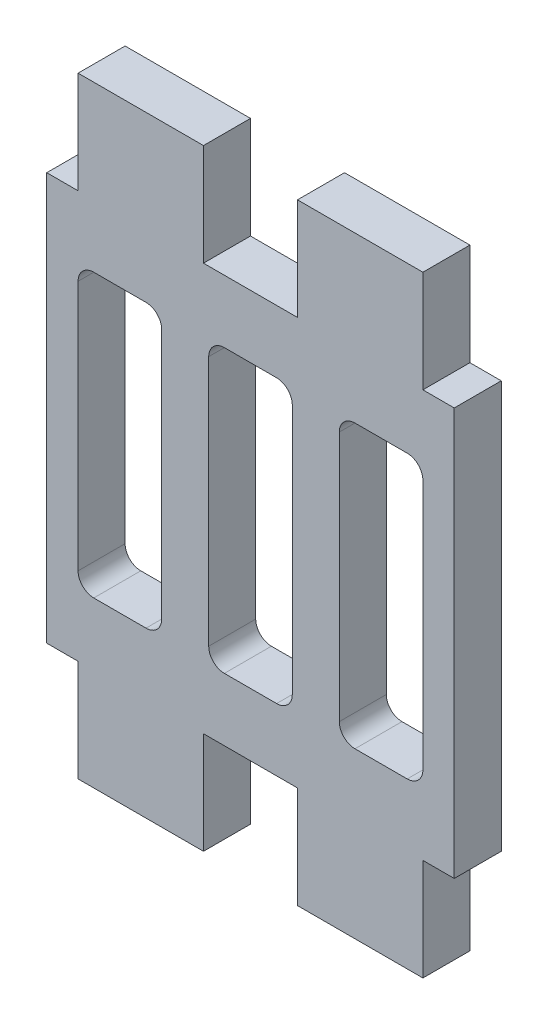
SolidWorks part; units mm, degrees
ref_plane "前视基准面" through (0, 0, 0) normal (0, 0, 1) x (1, 0, 0)
ref_plane "上视基准面" through (0, 0, 0) normal (0, 1, 0) x (1, 0, 0)
ref_plane "右视基准面" through (0, 0, 0) normal (1, 0, 0) x (0, 0, -1)
sketch "草图1" plane through (0, 0, 0) normal (0, 0, 1) x (1, 0, 0)
  line L0 (-11, 13) -> (-3, 13)
  line L1 (-13, 13) -> (13, 13)
  line L2 (-13, 13) -> (-13, -13)
  line L3 (-13, -13) -> (13, -13)
  line L4 (13, 13) -> (13, -13)
  line L5 (0, -13) -> (0, 13) construction
  line L6 (-13, 0) -> (13, 0) construction
  line L7 (-11, 13) -> (-11, 19.5)
  line L8 (-3, 13) -> (-3, 19.5)
  line L9 (-11, 19.5) -> (-3, 19.5)
  line L10 (3, 13) -> (11, 13)
  line L11 (3, 13) -> (3, 19.5)
  line L12 (11, 13) -> (11, 19.5)
  line L13 (3, 19.5) -> (11, 19.5)
  line L22 (3, -19.5) -> (11, -19.5)
  line L23 (11, -13) -> (11, -19.5)
  line L24 (3, -13) -> (3, -19.5)
  line L25 (3, -13) -> (11, -13)
  line L26 (-11, -19.5) -> (-3, -19.5)
  line L27 (-3, -13) -> (-3, -19.5)
  line L28 (-11, -13) -> (-11, -19.5)
  line L29 (-11, -13) -> (-3, -13)
  line L31 (-2.6667, 9) -> (2.6667, 9)
  line L32 (-2.6667, 9) -> (-2.6667, -9)
  line L33 (-2.6667, -9) -> (2.6667, -9)
  line L34 (2.6667, 9) -> (2.6667, -9)
  line L35 (0, -9) -> (0, 9) construction
  line L36 (-2.6667, 0) -> (2.6667, 0) construction
  line L37 (-11, 9) -> (-5.6667, 9)
  line L38 (-11, 9) -> (-11, -9)
  line L39 (-11, -9) -> (-5.6667, -9)
  line L40 (-5.6667, 9) -> (-5.6667, -9)
  line L41 (-8.3333, -9) -> (-8.3333, 9) construction
  line L42 (-11, 0) -> (-5.6667, 0) construction
  line L43 (5.6667, 9) -> (11, 9)
  line L44 (5.6667, 9) -> (5.6667, -9)
  line L45 (5.6667, -9) -> (11, -9)
  line L46 (11, 9) -> (11, -9)
  line L47 (8.3333, -9) -> (8.3333, 9) construction
  line L48 (5.6667, 0) -> (11, 0) construction
  point P0 (0, 0)
  point P28 (0, 0)
  point P32 (-8.3333, 0)
  point P36 (8.3333, 0)
  dimension "D1" = 6.5
  dimension "D2" = 6
  dimension "D3" = 2
  dimension "D4" = 2
  dimension "D6" = 8
  dimension "D7" = 26
  dimension "D8" = 3
  dimension "D9" = 3
  dimension "D10" = 2
  dimension "D11" = 4
extrude "凸台-拉伸1" add sketch "草图1" along normal blind 3
fillet "圆角2" radius 1 12 edges at (5.6667, -9, 1.5) (-2.6667, -9, 1.5) (-11, -9, 1.5) (11, 9, 1.5) (5.6667, 9, 1.5) (-2.6667, 9, 1.5) (2.6667, 9, 1.5) (-5.6667, 9, 1.5) (-11, 9, 1.5) (11, -9, 1.5) (2.6667, -9, 1.5) (-5.6667, -9, 1.5)
